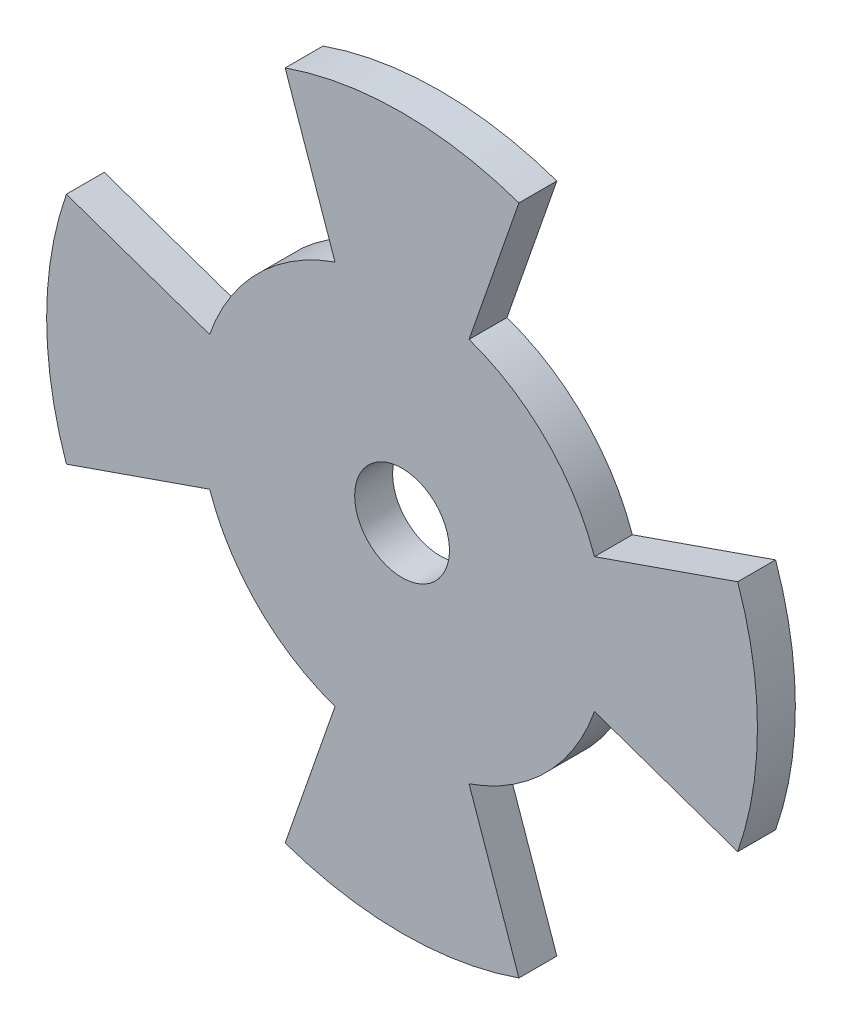
SolidWorks part; units mm, degrees
ref_plane "Front Plane" through (0, 0, 0) normal (0, 0, 1) x (1, 0, 0)
ref_plane "Top Plane" through (0, 0, 0) normal (0, 1, 0) x (1, 0, 0)
ref_plane "Right Plane" through (0, 0, 0) normal (1, 0, 0) x (0, 0, -1)
sketch "Sketch1" plane through (0, 0, 0) normal (0, 0, 1) x (1, 0, 0)
  line L0 (0, 18.75) -> (0, 22.9514) construction
  line L1 (3.5358, 10.1519) -> (6.167, 17.7068)
  line L2 (-3.5358, 10.1519) -> (-6.167, 17.7068)
  line L3 (-10.1519, -3.5358) -> (-17.7068, -6.167)
  line L4 (-10.1519, 3.5358) -> (-17.7068, 6.167)
  line L5 (3.5358, -10.1519) -> (6.167, -17.7068)
  line L6 (-3.5358, -10.1519) -> (-6.167, -17.7068)
  line L7 (10.1519, 3.5358) -> (17.7068, 6.167)
  line L8 (10.1519, -3.5358) -> (17.7068, -6.167)
  arc A0 (6.167, 17.7068) -> (-6.167, 17.7068) centre (0, 0) ccw
  arc A1 (-10.1519, -3.5358) -> (-3.5358, -10.1519) centre (0, 0) ccw
  circle A2 centre (0, 0) radius 10.75 construction
  arc A3 (-3.5358, 10.1519) -> (-10.1519, 3.5358) centre (0, 0) ccw
  arc A4 (10.1519, 3.5358) -> (3.5358, 10.1519) centre (0, 0) ccw
  arc A5 (3.5358, -10.1519) -> (10.1519, -3.5358) centre (0, 0) ccw
  circle A6 centre (0, 0) radius 18.75 construction
  arc A7 (-17.7068, 6.167) -> (-17.7068, -6.167) centre (0, 0) ccw
  arc A8 (-6.167, -17.7068) -> (6.167, -17.7068) centre (0, 0) ccw
  arc A9 (17.7068, -6.167) -> (17.7068, 6.167) centre (0, 0) ccw
  point P6 (-31.1799, 7.7289)
  point P15 (0, 0)
  dimension "D1" = 37.5
  dimension "D2" = 19.203
  dimension "D3" = 4
extrude "Boss-Extrude1" add sketch "Sketch1" along normal blind 2
sketch "Sketch2" plane through (0, 0, 0) normal (0, 0, -1) x (-1, 0, 0)
  circle A0 centre (0, 0) radius 2.5
  dimension "D1" = 5
extrude "Cut-Extrude1" cut sketch "Sketch2" against normal through all
